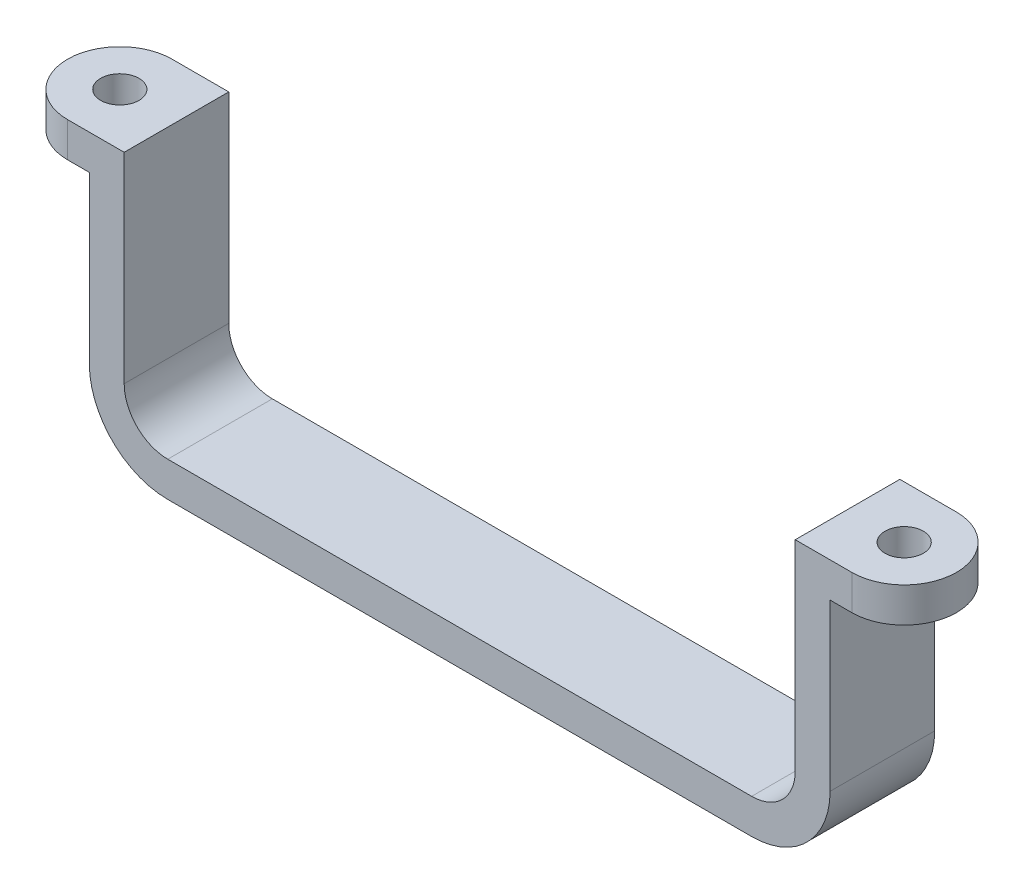
SolidWorks part; units mm, degrees
material "ABS"
ref_plane "Front Plane" through (0, 0, 0) normal (0, 0, 1) x (1, 0, 0)
ref_plane "Top Plane" through (0, 0, 0) normal (0, 1, 0) x (1, 0, 0)
ref_plane "Right Plane" through (0, 0, 0) normal (1, 0, 0) x (0, 0, -1)
sketch "Sketch1" plane through (0, 0, 0) normal (0, 0, 1) x (1, 0, 0)
  line L0 (-21.25, 14) -> (-21.25, 2.5)
  line L1 (-16.75, -2) -> (16.75, -2)
  line L2 (21.25, 14) -> (21.25, 2.5)
  line L4 (-19.25, 14) -> (-19.25, 2.5)
  line L5 (-16.75, 0) -> (16.75, 0)
  line L6 (19.25, 14) -> (19.25, 2.5)
  line L7 (-21.25, 14) -> (-19.25, 14)
  line L8 (19.25, 14) -> (21.25, 14)
  arc A0 (16.75, 0) -> (19.25, 2.5) centre (16.75, 2.5) ccw
  arc A1 (-19.25, 2.5) -> (-16.75, 0) centre (-16.75, 2.5) ccw
  arc A2 (-21.25, 2.5) -> (-16.75, -2) centre (-16.75, 2.5) ccw
  arc A3 (16.75, -2) -> (21.25, 2.5) centre (16.75, 2.5) ccw
  point P6 (0, 0)
  dimension "D3" = 38.5
  dimension "D2" = 14
  dimension "D1" = 2.5
  dimension "D5" = 14
  dimension "D4" = 2
extrude "Boss-Extrude1" add sketch "Sketch1" along normal blind 6
sketch "Sketch3" plane through (0, 14, 0) normal (0, 1, 0) x (-1, 0, 0)
  line L0 (-22.5, 3) -> (22.5, 3) construction
  line L1 (0, 6) -> (0, 0) construction
  line L2 (-16.75, 6) -> (-16.75, 0) construction
  line L3 (-21.25, 6) -> (-21.25, 0)
  line L5 (21.25, 6) -> (21.25, 0)
  line L6 (22.5, 0) -> (-22.5, 0)
  line L7 (-22.5, 6) -> (22.5, 6)
  circle A0 centre (-22.5, 3) radius 3
  circle A1 centre (-22.5, 3) radius 1.1
  circle A2 centre (22.5, 3) radius 1.1
  circle A3 centre (22.5, 3) radius 3
  point P1 (0, 3)
  point P13 (-16.75, 3)
  point P15 (0, 3)
  dimension "D2" = 2.2
  dimension "D3" = 6
extrude "Boss-Extrude6" add sketch "Sketch3" against normal blind 2
